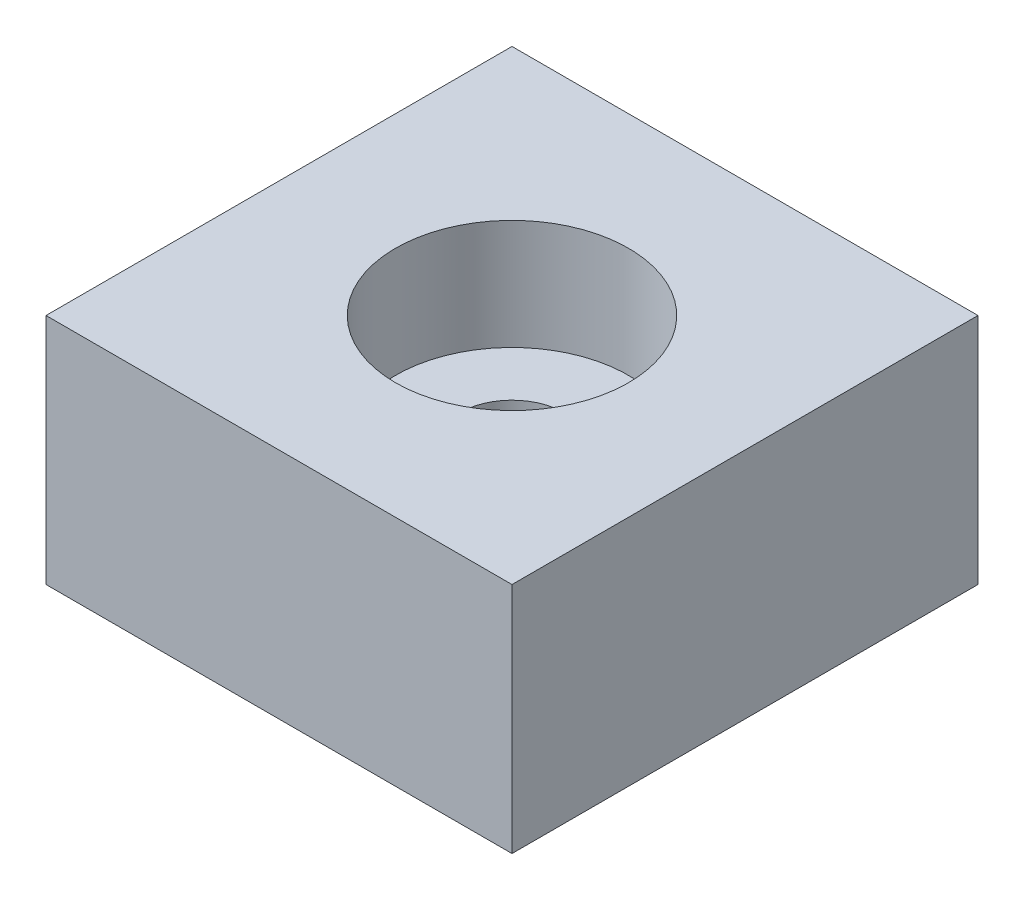
SolidWorks part; units mm, degrees
material "AISI 1020 Steel, Cold Rolled"
ref_plane "Front Plane" through (0, 0, 0) normal (0, 0, 1) x (1, 0, 0)
ref_plane "Top Plane" through (0, 0, 0) normal (0, 1, 0) x (1, 0, 0)
ref_plane "Right Plane" through (0, 0, 0) normal (1, 0, 0) x (0, 0, -1)
sketch "Sketch1" plane through (0, 0, 0) normal (0, 1, 0) x (1, 0, 0)
  line L1 (-19.05, -19.05) -> (19.05, -19.05)
  line L2 (-19.05, -19.05) -> (-19.05, 19.05)
  line L3 (-19.05, 19.05) -> (19.05, 19.05)
  line L4 (19.05, -19.05) -> (19.05, 19.05)
  line L5 (0, 19.05) -> (0, -19.05) construction
  line L6 (-19.05, 0) -> (19.05, 0) construction
  point P0 (0, 0)
  dimension "D1" = 38.1
extrude "Boss-Extrude1" add sketch "Sketch1" along normal blind 19.05
sketch "Sketch4" plane through (0, 19.05, 0) normal (0, 1, 0) x (1, 0, 0)
  point P0 (0, 0)
hole_wizard "M10x1.5 Tapped Hole1" positions "Sketch4" profile "Sketch3" tap size "M10x1.5" standard "ANSI Metric" end condition through all
sketch "Sketch3" plane through (0, 19.05, 0) normal (1, 0, 0) x (0, 0, 1)
  line L0 (0, 0) -> (0, 19.05)
  line L1 (0, 19.05) -> (4.25, 19.05)
  line L2 (4.25, 19.05) -> (4.25, 0)
  line L5 (4.25, 0) -> (0, 0)
  line L11 (0, -6.35) -> (0, 107.95) construction
  dimension "Thru Tap Drill Dia." = 8.5
  dimension "Thru Tap Drill Depth" = 19.05
cosmetic thread "Hole Thread1" parameters "D2"=10
sketch "Sketch5" plane through (0, 19.05, 0) normal (0, 1, 0) x (1, 0, 0)
  circle A0 centre (0, 0) radius 9.525
  point P2 (0, 0)
  dimension "D1" = 19.05
extrude "Cut-Extrude1" cut sketch "Sketch5" against normal blind 9
